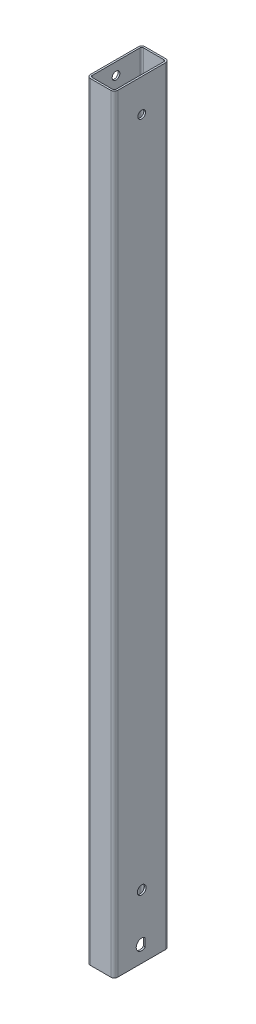
SolidWorks part; units mm, degrees
material "Plain Carbon Steel"
ref_plane "Front Plane" through (0, 0, 0) normal (0, 0, 1) x (1, 0, 0)
ref_plane "Top Plane" through (0, 0, 0) normal (0, 1, 0) x (1, 0, 0)
ref_plane "Right Plane" through (0, 0, 0) normal (1, 0, 0) x (0, 0, -1)
sketch "Sketch1" plane through (0, 0, 0) normal (1, 0, 0) x (0, 0, -1)
  line L1 (-25, -15) -> (25, -15)
  line L2 (-25, -15) -> (-25, 685)
  line L3 (-25, 685) -> (25, 685)
  line L4 (25, -15) -> (25, 685)
  line L5 (-25, -15) -> (25, 685) construction
  line L6 (-25, 685) -> (25, -15) construction
  circle A0 centre (0, 0) radius 5
  point P0 (0, 335)
  dimension "D1" = 10
  dimension "D2" = 15
  dimension "D3" = 700
  dimension "D4" = 50
extrude "Boss-Extrude1" add sketch "Sketch1" along normal mid plane 25
sketch "Sketch2" plane through (12.5, 0, 0) normal (1, 0, 0) x (0, 0, -1)
  line L1 (3, 4) -> (3, -4)
  circle A2 centre (0, 0) radius 5 construction
  arc A3 (3, -4) -> (3, 4) centre (0, 0) ccw
  dimension "D1" = 3
extrude "Boss-Extrude2" add sketch "Sketch2" against normal up to surface (25 mm away) up to face at (-12.5, 335, 0)
fillet "Fillet1" radius 1 2 edges at (0, 4, -3) (0, -4, -3)
sketch "Sketch3" plane through (12.5, 0, 0) normal (1, 0, 0) x (0, 0, -1)
  circle A0 centre (0, 20) radius 4
  dimension "D1" = 8
  dimension "D2" = 20
extrude "Cut-Extrude1" [suppressed] cut sketch "Sketch3" against normal through all
fillet "Fillet2" radius 3.2 4 edges at (-12.5, 335, -25) (12.5, 335, -25) (-12.5, 335, 25) (12.5, 335, 25)
sketch "Sketch4" plane through (0, -15, 0) normal (0, -1, 0) x (1, 0, 0)
  line L8 (-9.3, -23.4) -> (9.3, -23.4)
  line L9 (10.9, -21.8) -> (10.9, 21.8)
  line L10 (9.3, 23.4) -> (-9.3, 23.4)
  line L11 (-10.9, 21.8) -> (-10.9, -21.8)
  line L12 (-9.3, -23.4) -> (9.3, -23.4)
  line L13 (10.9, -21.8) -> (10.9, 21.8)
  line L14 (9.3, 23.4) -> (-9.3, 23.4)
  line L15 (-10.9, 21.8) -> (-10.9, -21.8)
  arc A8 (9.3, -23.4) -> (10.9, -21.8) centre (9.3, -21.8) ccw
  arc A9 (10.9, 21.8) -> (9.3, 23.4) centre (9.3, 21.8) ccw
  arc A10 (-9.3, 23.4) -> (-10.9, 21.8) centre (-9.3, 21.8) ccw
  arc A11 (-10.9, -21.8) -> (-9.3, -23.4) centre (-9.3, -21.8) ccw
  arc A12 (9.3, -23.4) -> (10.9, -21.8) centre (9.3, -21.8) ccw
  arc A13 (10.9, 21.8) -> (9.3, 23.4) centre (9.3, 21.8) ccw
  arc A14 (-9.3, 23.4) -> (-10.9, 21.8) centre (-9.3, 21.8) ccw
  arc A15 (-10.9, -21.8) -> (-9.3, -23.4) centre (-9.3, -21.8) ccw
  dimension "D1" = 1.6
extrude "Cut-Extrude2" cut sketch "Sketch4" against normal through all
sketch "Sketch5" plane through (12.5, 0, 0) normal (1, 0, 0) x (0, 0, -1)
  circle A0 centre (0, 43) radius 4
  dimension "D1" = 8
  dimension "D2" = 43
extrude "Cut-Extrude3" cut sketch "Sketch5" against normal up to next
sketch "Sketch6" plane through (12.5, 0, 0) normal (1, 0, 0) x (0, 0, -1)
  line L0 (21.8, 685) -> (-21.8, 685) construction
  circle A0 centre (0, 655) radius 3.5
  dimension "D1" = 30
  dimension "D2" = 7
extrude "Cut-Extrude4" cut sketch "Sketch6" against normal up to next
sketch "Sketch7" plane through (0, 0, -25) normal (0, 0, -1) x (-1, 0, 0)
  line L0 (0, 665) -> (0, 565) construction
  line L1 (-9.3, 685) -> (9.3, 685) construction
  circle A0 centre (0, 665) radius 5
  circle A1 centre (0, 565) radius 5
  dimension "D1" = 100
  dimension "D3" = 10
  dimension "D2" = 20
extrude "Cut-Extrude5" cut sketch "Sketch7" against normal up to next
sketch "Sketch8" plane through (-12.5, 0, 0) normal (-1, 0, 0) x (0, 0, 1)
  line L0 (0, 674) -> (0, 656) construction
  line L1 (-21.8, 685) -> (21.8, 685) construction
  circle A0 centre (0, 674) radius 3.5
  circle A1 centre (0, 656) radius 3.5
  point P6 (0, 685)
  point P8 (0, 665)
  dimension "D1" = 7
  dimension "D2" = 18
  dimension "D3" = 20
extrude "Cut-Extrude6" cut sketch "Sketch8" against normal up to next
